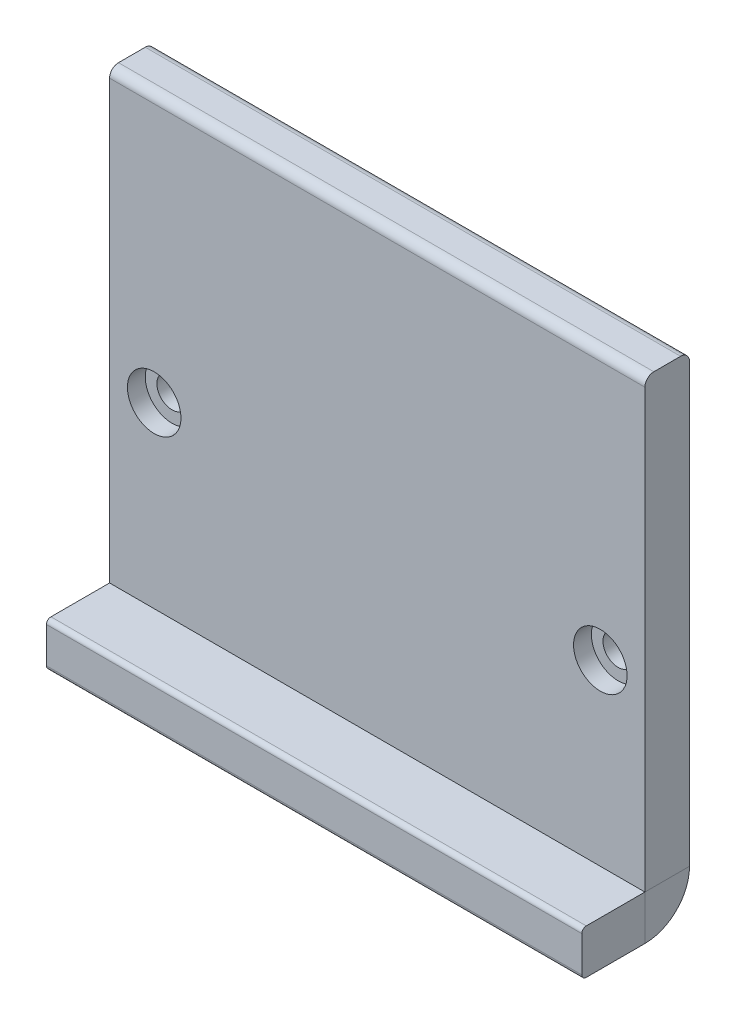
SolidWorks part; units mm, degrees
ref_plane "前视基准面" through (0, 0, 0) normal (0, 0, 1) x (1, 0, 0)
ref_plane "上视基准面" through (0, 0, 0) normal (0, 1, 0) x (1, 0, 0)
ref_plane "右视基准面" through (0, 0, 0) normal (1, 0, 0) x (0, 0, -1)
sketch "草图1" plane through (0, 0, 0) normal (0, 0, 1) x (1, 0, 0)
  line L1 (-30, -25) -> (30, -25)
  line L2 (-30, -25) -> (-30, 25)
  line L3 (-30, 25) -> (30, 25)
  line L4 (30, -25) -> (30, 25)
  line L5 (-30, -25) -> (30, 25) construction
  line L6 (-30, 25) -> (30, -25) construction
  point P0 (0, 0)
  dimension "D1" = 50
  dimension "D2" = 60
extrude "凸台-拉伸1" add sketch "草图1" along normal blind 5
hole_wizard "打孔尺寸(%根据)内六角圆柱头螺钉的类型1" positions "草图2" profile "草图3" counterbore size "M3" standard "GB"
sketch "草图2" plane through (0, 0, 5) normal (0, 0, 1) x (1, 0, 0)
  line L0 (-30, -25) -> (30, -25) construction
  line L1 (-30, 25) -> (-30, -25) construction
  line L2 (30, -25) -> (30, 25) construction
  point P0 (-25, -5)
  point P2 (25, -5)
  dimension "D1" = 20
  dimension "D2" = 20
  dimension "D3" = 5
  dimension "D4" = 5
sketch "草图3" plane through (-25, -5, 5) normal (1, 0, 0) x (0, -1, 0)
  line L0 (0, 0) -> (0, 7)
  line L1 (0, 7) -> (1.7, 7)
  line L2 (1.7, 7) -> (1.7, 2)
  line L3 (1.7, 2) -> (3, 2)
  line L4 (3, 2) -> (3, 0)
  line L5 (3, 0) -> (0, 0)
  line L10 (0, 7) -> (-1.7, 7) construction
  line L11 (0, -6.35) -> (0, 107.95) construction
  dimension "孔直径" = 3.4
  dimension "孔深度" = 7
  dimension "柱形沉头孔直径" = 6
  dimension "柱形沉头孔深度" = 2
  dimension "导头角度" = 180
sketch "草图4" plane through (-30, 0, 0) normal (-1, 0, 0) x (0, 0, 1)
  line L0 (5, -25) -> (12.07, -25)
  line L1 (5, 25) -> (5, -25) construction
  line L2 (5, -25) -> (5, -30)
  line L3 (5, -30) -> (12.07, -30)
  line L4 (12.07, -30) -> (12.07, -25)
  dimension "D1" = 90
  dimension "D2" = 7.07
  dimension "D3" = 5
extrude "凸台-拉伸2" add sketch "草图4" against normal blind 60 separate body
sketch "草图5" plane through (-30, 0, 0) normal (-1, 0, 0) x (0, 0, 1)
  line L2 (5, -30) -> (5, -25)
  line L3 (5, -25) -> (0, -25)
  arc A0 (0, -25) -> (5, -30) centre (5, -25) ccw
extrude "凸台-拉伸3" add sketch "草图5" against normal blind 60 separate body
sketch "草图7" plane through (-30, 0, 0) normal (-1, 0, 0) x (0, 0, 1)
  line L0 (5, 25) -> (0, 25) construction
  line L1 (4, 25) -> (5, 25)
  line L2 (5, 25) -> (5, 24)
  line L3 (5, 25) -> (5, -25) construction
  line L4 (0, 24) -> (0, 25)
  line L5 (0, 25) -> (0, -25) construction
  line L6 (0, 25) -> (1, 25)
  arc A0 (5, 24) -> (4, 25) centre (4, 24) ccw
  arc A1 (1, 25) -> (0, 24) centre (1, 24) ccw
  point P16 (4.4813, 24.5626)
  dimension "D1" = 1
  dimension "D2" = 1
  dimension "D3" = 1
  dimension "D4" = 1
extrude "切除-拉伸2" cut sketch "草图7" against normal through all
sketch "草图8" plane through (-30, 0, 0) normal (-1, 0, 0) x (0, 0, 1)
  line L0 (11.57, -25) -> (12.07, -25)
  line L1 (12.07, -25) -> (5, -25) construction
  line L2 (12.07, -25) -> (12.07, -25.5)
  line L3 (12.07, -30) -> (12.07, -25) construction
  line L4 (12.07, -29.5) -> (12.07, -30)
  line L5 (12.07, -30) -> (11.57, -30)
  line L6 (5, -30) -> (12.07, -30) construction
  arc A0 (12.07, -25.5) -> (11.57, -25) centre (11.57, -25.5) ccw
  arc A1 (11.57, -30) -> (12.07, -29.5) centre (11.57, -29.5) ccw
  dimension "D1" = 0.5
  dimension "D2" = 0.5
  dimension "D3" = 0.5
  dimension "D4" = 0.5
extrude "切除-拉伸3" cut sketch "草图8" against normal blind 60
